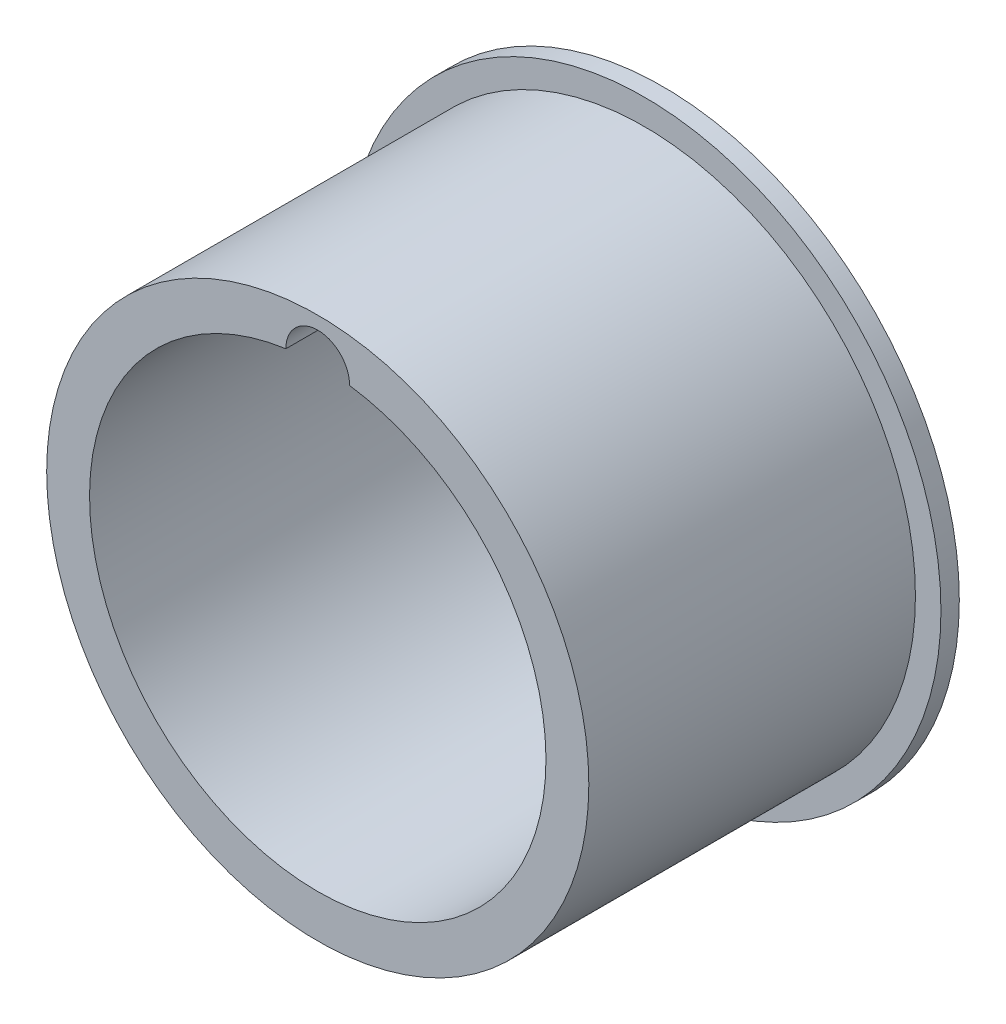
SolidWorks part; units mm, degrees
ref_plane "Front Plane" through (0, 0, 0) normal (0, 0, 1) x (1, 0, 0)
ref_plane "Top Plane" through (0, 0, 0) normal (0, 1, 0) x (1, 0, 0)
ref_plane "Right Plane" through (0, 0, 0) normal (1, 0, 0) x (0, 0, -1)
sketch "Sketch1" plane through (0, 0, 0) normal (0, 0, 1) x (1, 0, 0)
  circle A0 centre (0, 0) radius 28.3972
  circle A1 centre (0, 0) radius 33.7312
  dimension "D1" = 5.334
extrude "Boss-Extrude1" add sketch "Sketch1" along normal blind 40.64 and the other way blind 0.254
sketch "Sketch3" plane through (0, 0, 0) normal (0, 0, 1) x (1, 0, 0)
  circle A0 centre (0, 0) radius 36.9062
  circle A1 centre (0, 0) radius 33.7312 construction
  circle A2 centre (0, 0) radius 28.1445
  dimension "D1" = 3.175
extrude "Boss-Extrude2" add sketch "Sketch3" against normal blind 2.286
sketch "Sketch5" plane through (0, 0, 0) normal (0, 0, 1) x (1, 0, 0)
  circle A0 centre (0, 28.1445) radius 3.9625
  circle A1 centre (0, 0) radius 28.1445 construction
extrude "Cut-Extrude4" cut sketch "Sketch5" along normal blind 70.866 and the other way blind 4.064
